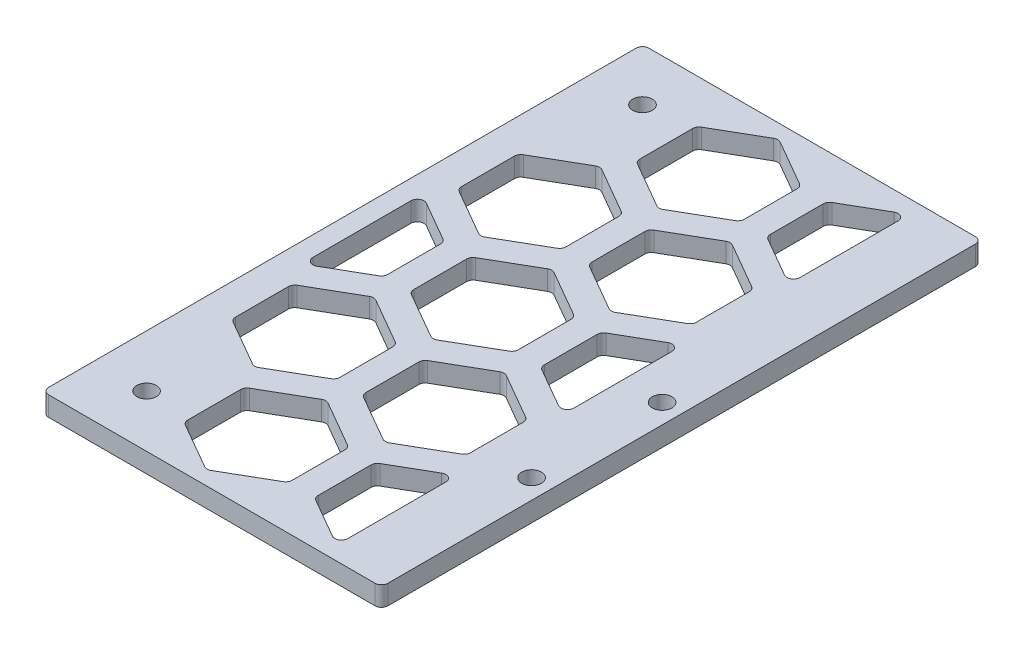
SolidWorks part; units mm, degrees
ref_plane "前视基准面" through (0, 0, 0) normal (0, 0, 1) x (1, 0, 0)
ref_plane "上视基准面" through (0, 0, 0) normal (0, 1, 0) x (1, 0, 0)
ref_plane "右视基准面" through (0, 0, 0) normal (1, 0, 0) x (0, 0, -1)
other "Configuration Table"
sketch "草图1" plane through (0, 0, 0) normal (0, 1, 0) x (1, 0, 0)
  line L0 (49, 46) -> (49, 26) construction
  line L1 (0, 0) -> (52, 0)
  line L2 (0, 0) -> (0, 92)
  line L3 (0, 92) -> (52, 92)
  line L4 (52, 0) -> (52, 92)
  line L5 (52, 46) -> (0, 46) construction
  line L6 (8, 84) -> (8, 8) construction
  circle A0 centre (49, 46) radius 1.5
  circle A1 centre (49, 26) radius 1.5
  circle A2 centre (8, 84) radius 1.5
  circle A3 centre (8, 8) radius 1.5
  point P15 (8, 46)
  dimension "D4" = 3
  dimension "D6" = 3
  dimension "D1" = 92
  dimension "D2" = 52
  dimension "D3" = 20
  dimension "D5" = 3
  dimension "D7" = 8
  dimension "D8" = 8
extrude "凸台-拉伸1" add sketch "草图1" along normal blind 3
fillet "圆角1" radius 1 4 edges at (0, 1.5, -92) (52, 1.5, -92) (0, 1.5, 0) (52, 1.5, 0)
sketch "草图2" plane through (0, 3, 0) normal (0, 1, 0) x (1, 0, 0)
  line L0 (3, 92) -> (3, 0) construction
  line L13 (23, 89.8786) -> (15, 85.2598)
  line L14 (15, 85.2598) -> (15, 76.0222)
  line L15 (15, 76.0222) -> (23, 71.4034)
  line L16 (23, 71.4034) -> (31, 76.0222)
  line L17 (31, 76.0222) -> (31, 85.2598)
  line L18 (31, 85.2598) -> (23, 89.8786)
  line L19 (13, 72.5581) -> (5, 67.9393)
  line L20 (5, 67.9393) -> (5, 58.7017)
  line L21 (5, 58.7017) -> (13, 54.0829)
  line L22 (13, 54.0829) -> (21, 58.7017)
  line L23 (21, 58.7017) -> (21, 67.9393)
  line L24 (21, 67.9393) -> (13, 72.5581)
  line L25 (51, 92) -> (1, 92) construction
  line L26 (1, 0) -> (51, 0) construction
  line L27 (0, 91) -> (0, 1) construction
  line L28 (43, 92) -> (43, 0) construction
  line L29 (52, 1) -> (52, 91) construction
  line L30 (23, 0) -> (23, 92) construction
  line L37 (43, 89.8786) -> (35, 85.2598)
  line L38 (35, 85.2598) -> (35, 76.0222)
  line L39 (35, 76.0222) -> (43, 71.4034)
  line L43 (23, 55.2376) -> (15, 50.6188)
  line L44 (15, 50.6188) -> (15, 41.3812)
  line L45 (15, 41.3812) -> (23, 36.7624)
  line L46 (23, 36.7624) -> (31, 41.3812)
  line L47 (31, 41.3812) -> (31, 50.6188)
  line L48 (31, 50.6188) -> (23, 55.2376)
  line L58 (3, 36.7624) -> (11, 41.3812)
  line L59 (11, 41.3812) -> (11, 50.6188)
  line L60 (11, 50.6188) -> (3, 55.2376)
  line L61 (23, 80.641) -> (43, 80.641) construction
  line L62 (43, 89.8786) -> (43, 71.4034)
  line L63 (3, 55.2376) -> (3, 36.7624)
  line L64 (35, 50.6188) -> (43, 55.2376)
  line L65 (35, 41.3812) -> (35, 50.6188)
  line L66 (43, 36.7624) -> (35, 41.3812)
  line L67 (43, 55.2376) -> (43, 36.7624)
  line L68 (25, 67.9393) -> (33, 72.5581)
  line L69 (51, 76.0222) -> (51, 85.2598) [skipped]
  line L70 (47, 87.5692) -> (43, 89.8786) [skipped]
  line L71 (43, 71.4034) -> (47, 73.7128) [skipped]
  line L72 (-1, 39.0718) -> (3, 36.7624) [skipped]
  line L73 (3, 55.2376) -> (-1, 52.9282) [skipped]
  line L74 (-5, 50.6188) -> (-5, 41.3812) [skipped]
  line L75 (25, 58.7017) -> (25, 67.9393)
  line L76 (33, 54.0829) -> (25, 58.7017)
  line L77 (41, 58.7017) -> (33, 54.0829)
  line L78 (41, 67.9393) -> (41, 58.7017)
  line L79 (33, 72.5581) -> (41, 67.9393)
  line L80 (23, 46) -> (52, 46) construction
  line L81 (21, 24.0607) -> (13, 19.4419)
  line L82 (21, 33.2983) -> (21, 24.0607)
  line L83 (13, 37.9171) -> (21, 33.2983)
  line L84 (5, 33.2983) -> (13, 37.9171)
  line L85 (5, 24.0607) -> (5, 33.2983)
  line L86 (13, 19.4419) -> (5, 24.0607)
  line L87 (25, 33.2983) -> (25, 24.0607)
  line L88 (33, 37.9171) -> (25, 33.2983)
  line L89 (41, 33.2983) -> (33, 37.9171)
  line L90 (41, 24.0607) -> (41, 33.2983)
  line L91 (33, 19.4419) -> (41, 24.0607)
  line L92 (25, 24.0607) -> (33, 19.4419)
  line L93 (43, 2.1214) -> (35, 6.7402)
  line L94 (35, 6.7402) -> (35, 15.9778)
  line L95 (35, 15.9778) -> (43, 20.5966)
  line L96 (43, 2.1214) -> (43, 20.5966)
  line L97 (31, 6.7402) -> (23, 2.1214)
  line L98 (31, 15.9778) -> (31, 6.7402)
  line L99 (23, 20.5966) -> (31, 15.9778)
  line L100 (15, 15.9778) -> (23, 20.5966)
  line L101 (15, 6.7402) -> (15, 15.9778)
  line L102 (23, 2.1214) -> (15, 6.7402)
  circle A0 centre (23, 80.641) radius 8 construction
  circle A1 centre (13, 63.3205) radius 8 construction
  arc A3 (43, 88.641) -> (43, 72.641) centre (43, 80.641) ccw construction
  circle A4 centre (23, 46) radius 8 construction
  arc A6 (3, 38) -> (3, 54) centre (3, 46) ccw construction
  point P69 (3, 46)
  dimension "D1" = 3
  dimension "D2" = 9
  dimension "D3" = 20
  dimension "D4" = 16
  dimension "D5" = 4
  dimension "D6" = 4
  dimension "D7" = 4
extrude "切除-拉伸1" cut sketch "草图2" against normal blind 10
fillet "圆角2" radius 1 58 edges at (31, 1.5, -85.2598) (31, 1.5, -76.0222) (23, 1.5, -71.4034) (15, 1.5, -76.0222) (15, 1.5, -85.2598) (31, 1.5, -6.7402) (23, 1.5, -2.1214) (15, 1.5, -6.7402) (15, 1.5, -15.9778) (23, 1.5, -20.5966) (31, 1.5, -15.9778) (43, 1.5, -2.1214) (35, 1.5, -6.7402) (35, 1.5, -15.9778) (43, 1.5, -20.5966) (35, 1.5, -50.6188) (43, 1.5, -55.2376) (43, 1.5, -36.7624) (35, 1.5, -41.3812) (21, 1.5, -24.0607) (13, 1.5, -19.4419) (5, 1.5, -24.0607) (5, 1.5, -33.2983) (13, 1.5, -37.9171) (21, 1.5, -33.2983) (43, 1.5, -71.4034) (35, 1.5, -76.0222) (35, 1.5, -85.2598) (43, 1.5, -89.8786) (21, 1.5, -67.9393) (21, 1.5, -58.7017) (13, 1.5, -54.0829) (5, 1.5, -58.7017) (5, 1.5, -67.9393) (13, 1.5, -72.5581) (33, 1.5, -37.9171) (41, 1.5, -33.2983) (41, 1.5, -24.0607) (33, 1.5, -19.4419) (25, 1.5, -24.0607) (25, 1.5, -33.2983) (3, 1.5, -55.2376) (11, 1.5, -50.6188) (11, 1.5, -41.3812) (3, 1.5, -36.7624) (25, 1.5, -67.9393) (33, 1.5, -72.5581) (41, 1.5, -67.9393) (41, 1.5, -58.7017) (33, 1.5, -54.0829) (25, 1.5, -58.7017) (31, 1.5, -50.6188) (31, 1.5, -41.3812) (23, 1.5, -36.7624) (15, 1.5, -41.3812) (15, 1.5, -50.6188) (23, 1.5, -55.2376) (23, 1.5, -89.8786)
